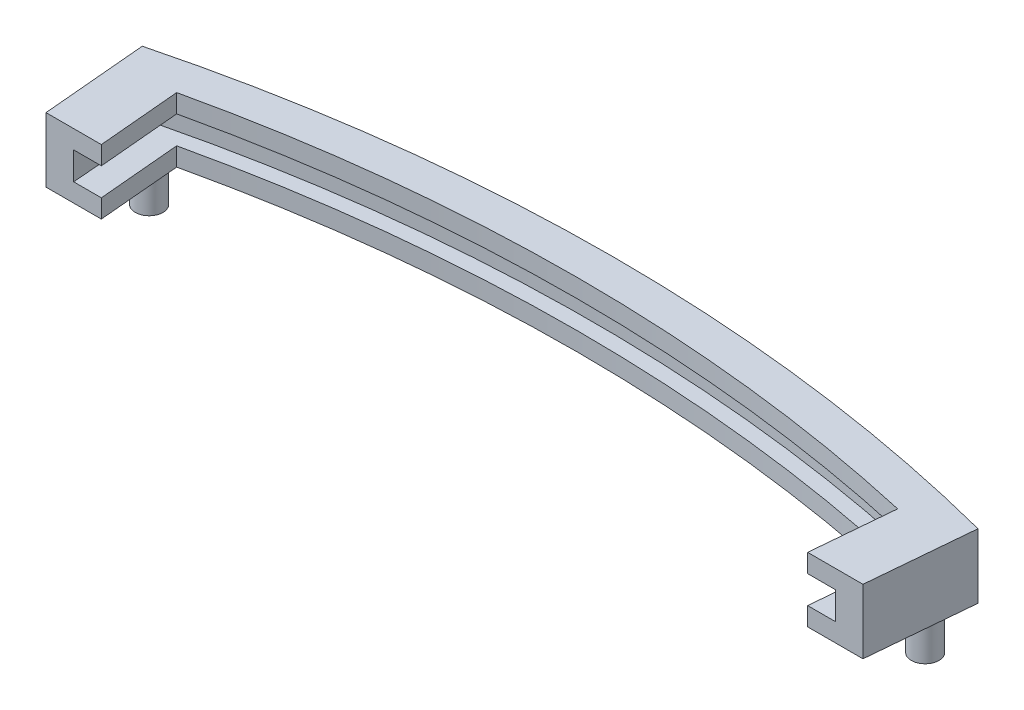
SolidWorks part; units mm, degrees
ref_plane "Front Plane" through (0, 0, 0) normal (0, 0, 1) x (1, 0, 0)
ref_plane "Top Plane" through (0, 0, 0) normal (0, 1, 0) x (1, 0, 0)
ref_plane "Right Plane" through (0, 0, 0) normal (1, 0, 0) x (0, 0, -1)
sketch "Sketch2" plane through (0, 0, 0) normal (0, 1, 0) x (1, 0, 0)
  line L18 (-44.2925, 163.9991) -> (-38.2925, 163.9991)
  line L23 (38.2925, 163.9991) -> (44.2925, 163.9991)
  line L24 (-44.2925, 163.9991) -> (-45.3108, 175.4539)
  line L27 (38.2925, 163.9991) -> (39.0895, 172.9637)
  line L28 (-38.2925, 163.9991) -> (-39.0895, 172.9637)
  line L31 (44.2925, 163.9991) -> (45.3108, 175.4539)
  arc A6 (45.3108, 175.4539) -> (-45.3108, 175.4539) centre (0, 0) ccw
  arc A7 (39.0895, 172.9637) -> (-39.0895, 172.9637) centre (0, 0) ccw
  dimension "D1" = 181.2102
  dimension "D2" = 177.3258
  dimension "D5" = 6
  dimension "D7" = 11.5
  dimension "D8" = 9
extrude "Boss-Extrude4" add sketch "Sketch2" along normal blind 2 contours A7 L28 L18 L24 A6 L31 L23 L27
sketch "Sketch5" plane through (0, 2, 0) normal (0, 1, 0) x (1, 0, 0)
  line L0 (-41.2925, 163.9991) -> (-42.1027, 173.978)
  line L1 (-44.2925, 163.9991) -> (-38.2925, 163.9991) construction
  line L2 (-41.2925, 163.9991) -> (-44.2925, 163.9991)
  line L3 (-44.2925, 163.9991) -> (-45.3108, 175.4539)
  line L4 (41.2925, 163.9991) -> (44.2925, 163.9991)
  line L5 (44.2925, 163.9991) -> (45.3108, 175.4539)
  line L6 (38.2925, 163.9991) -> (44.2925, 163.9991) construction
  line L7 (41.2925, 163.9991) -> (42.178, 173.9598)
  arc A0 (42.178, 173.9598) -> (-42.1027, 173.978) centre (0, 0) ccw
  arc A1 (45.3108, 175.4539) -> (-45.3108, 175.4539) centre (0, 0) ccw
  dimension "D1" = 358
extrude "Boss-Extrude5" add sketch "Sketch5" along normal blind 3
sketch "Sketch6" plane through (0, 5, 0) normal (0, 1, 0) x (1, 0, 0)
  line L0 (-44.2925, 163.9991) -> (-38.2925, 163.9991)
  line L1 (-38.2925, 163.9991) -> (-39.0895, 172.9637)
  line L2 (-44.2925, 163.9991) -> (-45.3108, 175.4539)
  line L3 (39.0895, 172.9637) -> (38.2925, 163.9991)
  line L4 (38.2925, 163.9991) -> (44.2925, 163.9991)
  line L5 (44.2925, 163.9991) -> (45.3108, 175.4539)
  arc A0 (39.0895, 172.9637) -> (-39.0895, 172.9637) centre (0, 0) ccw
  arc A1 (45.3108, 175.4539) -> (-45.3108, 175.4539) centre (0, 0) ccw
extrude "Boss-Extrude6" add sketch "Sketch6" along normal blind 2
sketch "Sketch7" plane through (0, 0, 0) normal (0, -1, 0) x (1, 0, 0)
  line L0 (0, -181.2102) -> (0, -163.1343) construction
  circle A0 centre (-42.0723, -172.9637) radius 1.5
  arc A1 (-45.3108, -175.4539) -> (45.3108, -175.4539) centre (0, 0) ccw construction
  circle A2 centre (42.0723, -172.9637) radius 1.5
  dimension "D1" = 3
extrude "Boss-Extrude7" add sketch "Sketch7" along normal blind 5 contours A0 | A2
